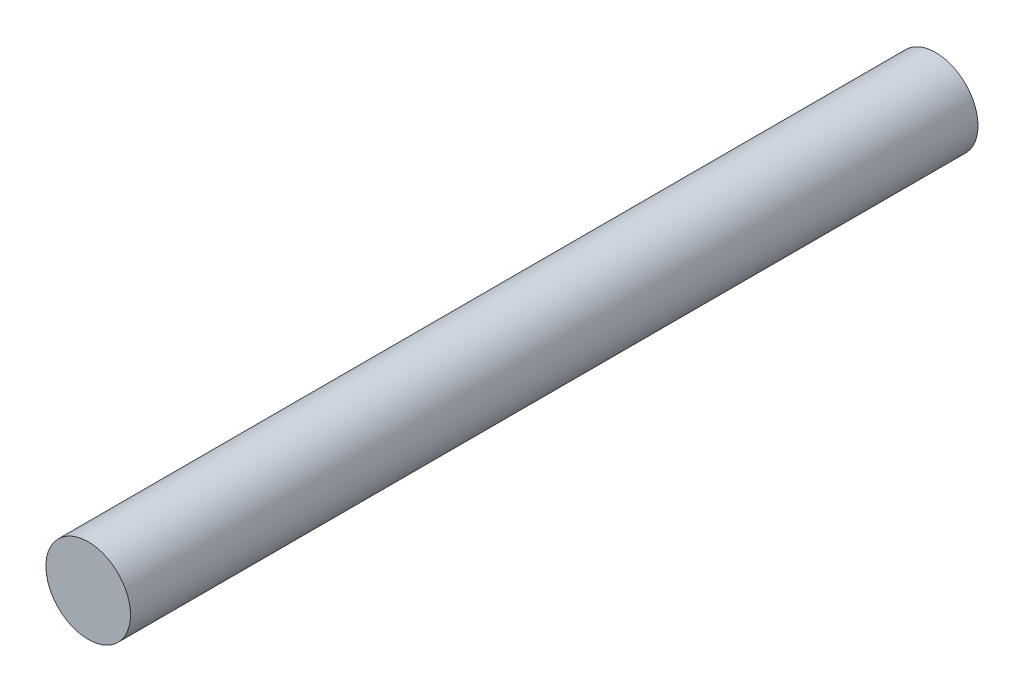
SolidWorks part; units mm, degrees
material "Pine"
ref_plane "Front Plane" through (0, 0, 0) normal (0, 0, 1) x (1, 0, 0)
ref_plane "Top Plane" through (0, 0, 0) normal (0, 1, 0) x (1, 0, 0)
ref_plane "Right Plane" through (0, 0, 0) normal (1, 0, 0) x (0, 0, -1)
sketch "Sketch1" plane through (0, 0, 0) normal (0, 0, 1) x (1, 0, 0)
  circle A0 centre (0, 0) radius 3.2385
  dimension "D1" = 6.477
extrude "Boss-Extrude1" add sketch "Sketch1" along normal blind 64.897
